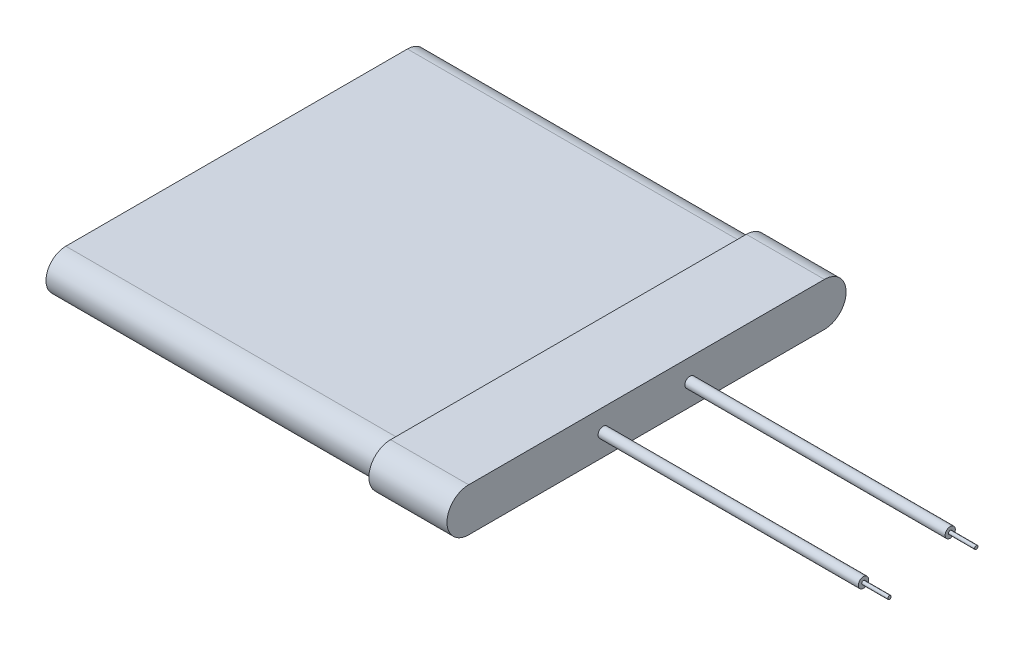
SolidWorks part; units mm, degrees
ref_plane "Front Plane" through (0, 0, 0) normal (0, 0, 1) x (1, 0, 0)
ref_plane "Top Plane" through (0, 0, 0) normal (0, 1, 0) x (1, 0, 0)
ref_plane "Right Plane" through (0, 0, 0) normal (1, 0, 0) x (0, 0, -1)
sketch "Sketch1" plane through (0, 0, 0) normal (1, 0, 0) x (0, 0, -1)
  line L0 (-25, 0) -> (25, 0) construction
  line L1 (-25, 2.9) -> (25, 2.9)
  line L2 (-25, -2.9) -> (25, -2.9)
  arc A0 (-25, 2.9) -> (-25, -2.9) centre (-25, 0) ccw
  arc A1 (25, -2.9) -> (25, 2.9) centre (25, 0) ccw
  point P2 (0, 0)
  dimension "D1" = 50
  dimension "D2" = 5.8
extrude "Boss-Extrude1" add sketch "Sketch1" along normal mid plane 60
sketch "Sketch2" plane through (30, 0, 0) normal (1, 0, 0) x (0, 0, -1)
  line L0 (-6.35, 0) -> (6.35, 0) construction
  circle A0 centre (-6.35, 0) radius 0.7493
  circle A1 centre (6.35, 0) radius 0.7493
  point P4 (0, 0)
  dimension "D2" = 1.4986
  dimension "D3" = 1.4986
  dimension "D1" = 12.7
extrude "Boss-Extrude2" add sketch "Sketch2" along normal blind 38.1
sketch "Sketch3" plane through (68.1, 0, 0) normal (1, 0, 0) x (0, 0, -1)
  circle A0 centre (-6.35, 0) radius 0.7493 construction
  circle A1 centre (6.35, 0) radius 0.7493 construction
  circle A2 centre (-6.35, 0) radius 0.7493
  circle A3 centre (6.35, 0) radius 0.7493
  circle A4 centre (-6.35, 0) radius 0.254
  circle A5 centre (6.35, 0) radius 0.254
  dimension "D1" = 0.508
extrude "Boss-Extrude3" add sketch "Sketch3" along normal blind 3.81 contours A4
sketch "Sketch5" plane through (68.1, 0, 0) normal (1, 0, 0) x (0, 0, -1)
  circle A1 centre (6.35, 0) radius 0.254
  dimension "D1" = 0.508
extrude "Boss-Extrude4" add sketch "Sketch5" along normal blind 3.81
sketch "Sketch6" plane through (30, 0, 0) normal (1, 0, 0) x (0, 0, -1)
  line L0 (26.035, 0) -> (-26.035, 0) construction
  line L1 (26.035, -3.175) -> (-26.035, -3.175)
  line L2 (-25, -2.9) -> (25, -2.9)
  line L3 (25, 2.9) -> (-25, 2.9)
  line L4 (-25, -2.9) -> (25, -2.9)
  line L5 (25, 2.9) -> (-25, 2.9)
  line L6 (26.035, 3.175) -> (-26.035, 3.175)
  arc A0 (26.035, -3.175) -> (26.035, 3.175) centre (26.035, 0) ccw
  arc A1 (-26.035, 3.175) -> (-26.035, -3.175) centre (-26.035, 0) ccw
  arc A2 (-25, 2.9) -> (-25, -2.9) centre (-25, 0) ccw
  arc A3 (25, -2.9) -> (25, 2.9) centre (25, 0) ccw
  arc A4 (-25, 2.9) -> (-25, -2.9) centre (-25, 0) ccw
  arc A5 (25, -2.9) -> (25, 2.9) centre (25, 0) ccw
  point P8 (0, 0)
  dimension "D2" = 52.07
  dimension "D3" = 6.35
  dimension "D1" = 0
extrude "Boss-Extrude6" add sketch "Sketch6" against normal blind 11.43 contours L6 A1 L1 A0
sketch "Sketch7" plane through (0, 2.9, 0) normal (0, 1, 0) x (1, 0, 0)
  text T0 "! E585460-4I21\r\nE4I04-L58-1\r\n+ 2000mAh 3.7V"
